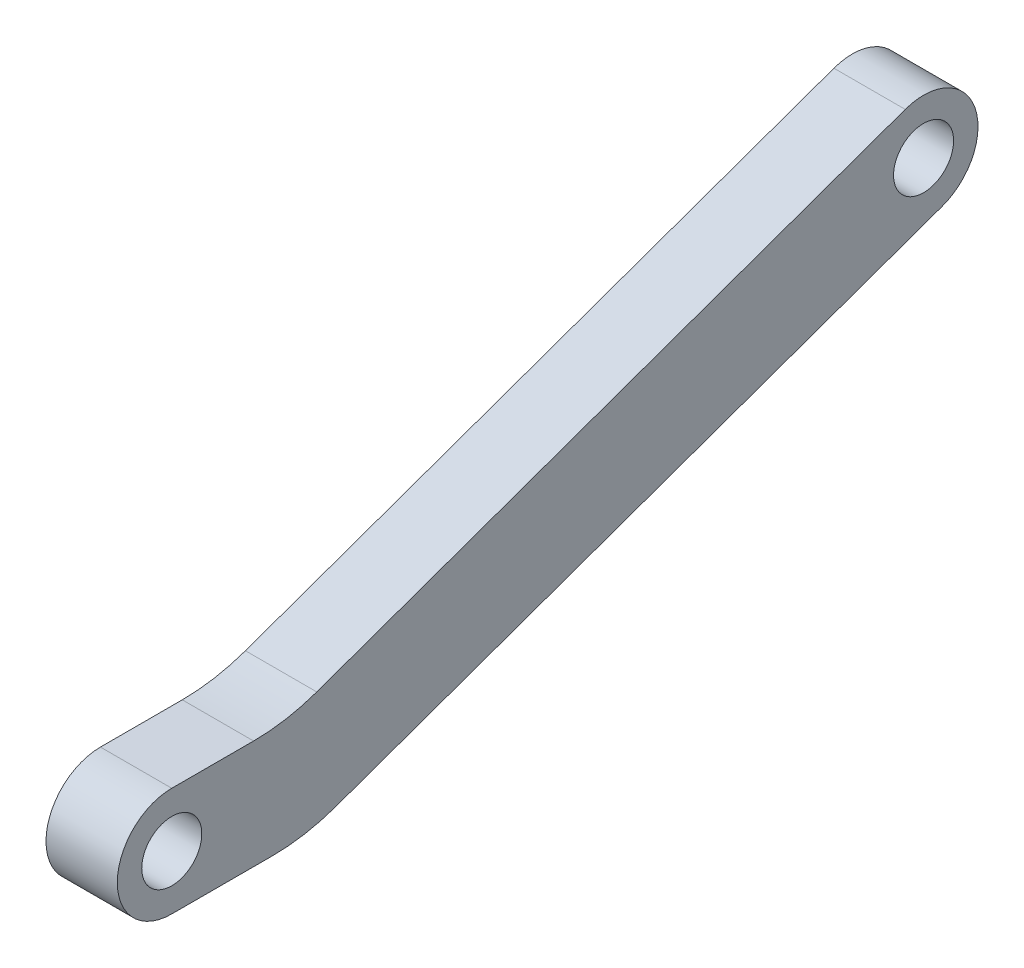
SolidWorks part; units mm, degrees
ref_plane "Front Plane" through (0, 0, 0) normal (0, 0, 1) x (1, 0, 0)
ref_plane "Top Plane" through (0, 0, 0) normal (0, 1, 0) x (1, 0, 0)
ref_plane "Right Plane" through (0, 0, 0) normal (1, 0, 0) x (0, 0, -1)
sketch "Sketch1" plane through (0, 0, 0) normal (1, 0, 0) x (0, 0, -1)
  line L0 (0, 0) -> (40.05, 11.95) construction
  line L1 (0, 2.9) -> (4.3595, 2.9)
  line L2 (0, -2.9) -> (5.3643, -2.9)
  line L7 (8.7281, -2.3173) -> (41.0255, 9.219)
  line L8 (7.7233, 3.4827) -> (39.0745, 14.681)
  circle A0 centre (0, 0) radius 1.6
  circle A1 centre (40.05, 11.95) radius 1.6
  arc A2 (0, 2.9) -> (0, -2.9) centre (0, 0) ccw
  arc A8 (41.0255, 9.219) -> (39.0745, 14.681) centre (40.05, 11.95) ccw
  arc A9 (5.3643, -2.9) -> (8.7281, -2.3173) centre (5.3643, 7.1) ccw
  arc A10 (4.3595, 2.9) -> (7.7233, 3.4827) centre (4.3595, 12.9) ccw
  point P22 (10, -2.9)
  dimension "D3" = 3.2
  dimension "D4" = 5.8
  dimension "D6" = 10
  dimension "D1" = 40.05
  dimension "D2" = 11.95
  dimension "D5" = 10
extrude "Boss-Extrude1" add sketch "Sketch1" along normal mid plane 3.8
